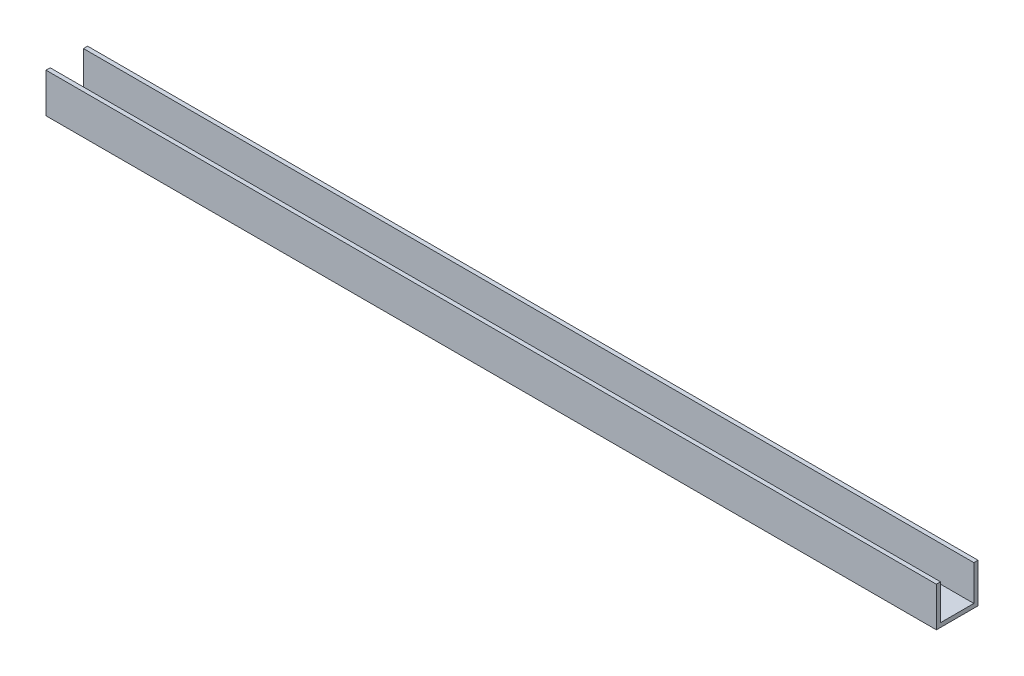
SolidWorks part; units mm, degrees
ref_plane "Plan de face" through (0, 0, 0) normal (0, 0, 1) x (1, 0, 0)
ref_plane "Plan de dessus" through (0, 0, 0) normal (0, 1, 0) x (1, 0, 0)
ref_plane "Plan de droite" through (0, 0, 0) normal (1, 0, 0) x (0, 0, -1)
sketch "Esquisse1" plane through (0, 0, 0) normal (1, 0, 0) x (0, 0, -1)
  line L0 (0, 0) -> (0, 2.6879) construction
  line L1 (-5, 9.5) -> (-4, 9.5)
  line L2 (-4, 1) -> (4, 1)
  line L3 (-4, 9.5) -> (-4, 1)
  line L4 (-5, 9.5) -> (-5, 0)
  line L5 (-5, 0) -> (5, 0)
  line L6 (5, 9.5) -> (5, 0)
  line L7 (4, 9.5) -> (4, 1)
  line L8 (5, 9.5) -> (4, 9.5)
  point P11 (0, 0)
  point P14 (0, 1)
  dimension "D1" = 1
  dimension "D2" = 1
  dimension "D3" = 5
  dimension "D4" = 9.5
extrude "Boss.-Extru.1" add sketch "Esquisse1" along normal mid plane 214
sketch "Esquisse2" plane through (0, 0, 0) normal (0, -1, 0) x (1, 0, 0)
  line L0 (0, 0) -> (132.2594, 0) construction
  line L1 (-88, 0) -> (-79, 0) construction
  line L2 (-79, 0) -> (-70, 0) construction
  line L3 (-107, 5) -> (-107, -5) construction
  circle A0 centre (-88, 0) radius 2.5
  circle A1 centre (-79, 0) radius 2.5
  circle A2 centre (-70, 0) radius 2.5
  circle A3 centre (-56, 0) radius 2.5
  circle A4 centre (-47, 0) radius 2.5
  circle A5 centre (-38, 0) radius 2.5
  circle A6 centre (-24, 0) radius 2.5
  circle A7 centre (-15, 0) radius 2.5
  circle A8 centre (-6, 0) radius 2.5
  circle A9 centre (8, 0) radius 2.5
  circle A10 centre (17, 0) radius 2.5
  circle A11 centre (26, 0) radius 2.5
  circle A12 centre (40, 0) radius 2.5
  circle A13 centre (49, 0) radius 2.5
  circle A14 centre (58, 0) radius 2.5
  circle A15 centre (72, 0) radius 2.5
  circle A16 centre (81, 0) radius 2.5
  circle A17 centre (90, 0) radius 2.5
  dimension "D3" = 5
  dimension "D1" = 18
  dimension "D2" = 19
  dimension "D5" = 32
  dimension "D4" = 6
extrude "Enlèv. mat.-Extru.1" cut sketch "Esquisse2" against normal through all
